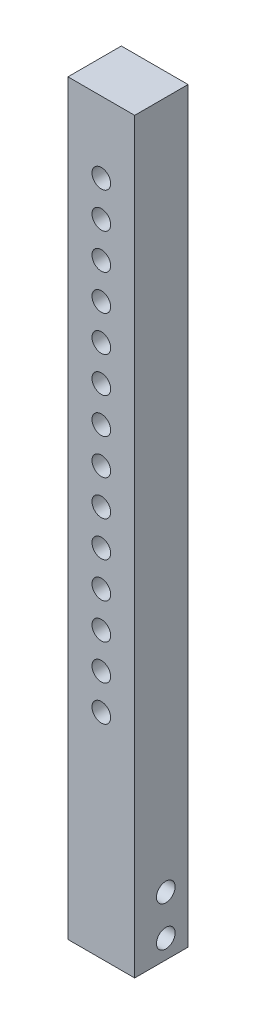
SolidWorks part; units mm, degrees
ref_plane "前视基准面" through (0, 0, 0) normal (0, 0, 1) x (1, 0, 0)
ref_plane "上视基准面" through (0, 0, 0) normal (0, 1, 0) x (1, 0, 0)
ref_plane "右视基准面" through (0, 0, 0) normal (1, 0, 0) x (0, 0, -1)
other "Configuration Table"
sketch "草图1" plane through (0, 0, 0) normal (0, 0, 1) x (1, 0, 0)
  line L1 (7.5, -85) -> (-7.5, -85)
  line L2 (7.5, -85) -> (7.5, 85)
  line L3 (7.5, 85) -> (-7.5, 85)
  line L4 (-7.5, -85) -> (-7.5, 85)
  line L5 (7.5, -85) -> (-7.5, 85) construction
  line L6 (7.5, 85) -> (-7.5, -85) construction
  point P0 (0, 0)
  dimension "D1" = 15
  dimension "D2" = 170
extrude "凸台-拉伸1" add sketch "草图1" along normal blind 12
sketch "草图2" plane through (0, -85, 0) normal (0, -1, 0) x (1, 0, 0)
  line L1 (-7.5, 0) -> (7.5, 0) construction
  line L2 (-5.55, 0) -> (2.55, 0)
  line L3 (-5.55, 0) -> (-5.55, 10.1)
  line L4 (-5.55, 10.1) -> (2.55, 10.1)
  line L5 (2.55, 0) -> (2.55, 10.1)
  line L6 (-7.5, 12) -> (-7.5, 0) construction
  point P0 (-1.5, 10.1)
  dimension "D1" = 10.1
  dimension "D2" = 8.1
  dimension "D3" = 6
extrude "切除-拉伸1" cut sketch "草图2" against normal blind 20.5
sketch "草图3" plane through (7.5, 0, 0) normal (1, 0, 0) x (0, 0, -1)
  line L0 (0, -85) -> (0, 85) construction
  line L1 (-12, -85) -> (0, -85) construction
  circle A0 centre (-5, -69.75) radius 2.1
  circle A1 centre (-5, -78.75) radius 2.1
  dimension "D1" = 4.2
  dimension "D2" = 5
  dimension "D3" = 5
  dimension "D4" = 15.25
  dimension "D5" = 9
extrude "切除-拉伸2" cut sketch "草图3" against normal up to surface (15 mm away) up to face at (-7.5, 0, 6)
sketch "草图5" plane through (0, 0, 12) normal (0, 0, 1) x (1, 0, 0)
  line L0 (-7.5, -85) -> (7.5, -85) construction
  line L1 (7.5, -85) -> (7.5, 85) construction
  circle A0 centre (0, -27) radius 2.1
  circle A1 centre (0, -35) radius 2.1
  circle A2 centre (0, -19) radius 2.1
  circle A3 centre (0, -11) radius 2.1
  circle A4 centre (0, -3) radius 2.1
  circle A5 centre (0, 5) radius 2.1
  circle A6 centre (0, 13) radius 2.1
  circle A7 centre (0, 21) radius 2.1
  circle A8 centre (0, 29) radius 2.1
  circle A9 centre (0, 37) radius 2.1
  circle A10 centre (0, 45) radius 2.1
  circle A11 centre (0, 53) radius 2.1
  circle A12 centre (0, 61) radius 2.1
  circle A13 centre (0, 69) radius 2.1
  dimension "D1" = 4.2
  dimension "D2" = 50
  dimension "D3" = 7.5
  dimension "D4" = 7.5
  dimension "D5" = 8
  dimension "D6" = 7
extrude "切除-拉伸3" cut sketch "草图5" against normal up to surface (12 mm away) up to face at (-0.75, -37.375, 0)
sketch "草图6" plane through (0, -85, 0) normal (0, -1, 0) x (1, 0, 0)
  line L1 (-7.5, 0) -> (7.5, 0)
  line L2 (-7.5, 0) -> (-7.5, 12)
  line L3 (-7.5, 12) -> (7.5, 12)
  line L4 (7.5, 0) -> (7.5, 12)
extrude "切除-拉伸4" cut sketch "草图6" against normal blind 2
